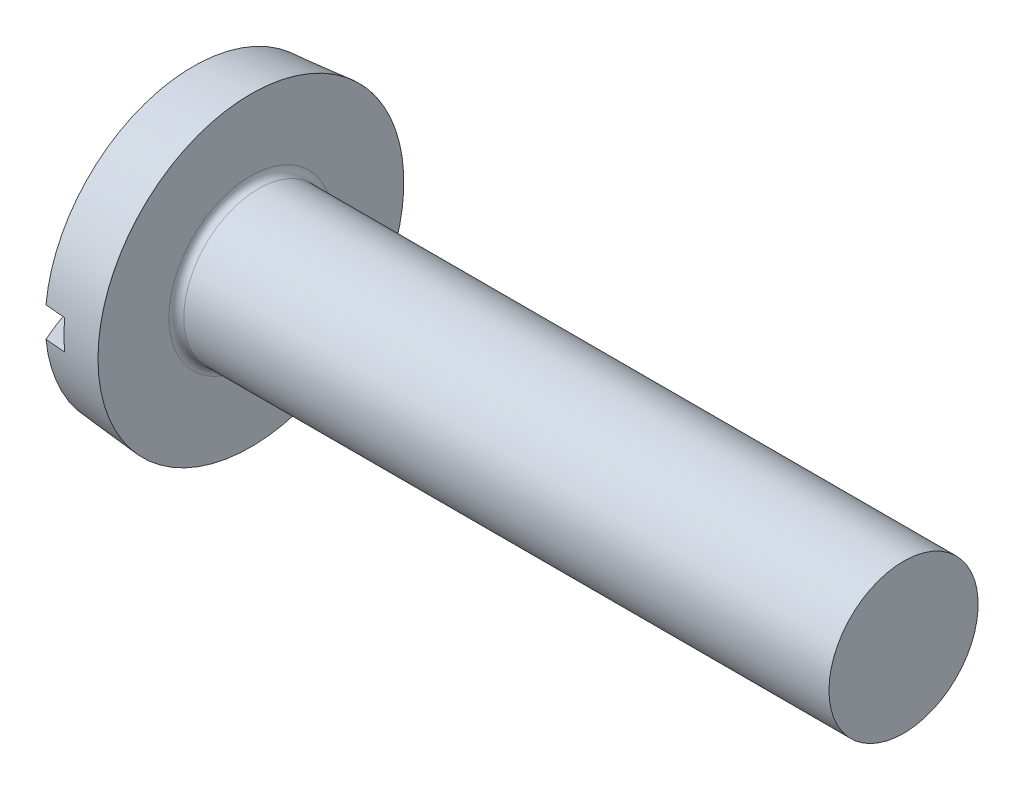
SolidWorks part; units mm, degrees
ref_plane "Plane1" through (0, 0, 0) normal (0, 0, 1) x (1, 0, 0)
ref_plane "Plane2" through (0, 0, 0) normal (0, 1, 0) x (1, 0, 0)
ref_plane "Plane3" through (0, 0, 0) normal (1, 0, 0) x (0, 0, -1)
sketch "BodySke" plane through (0, 0, 0) normal (0, 0, 1) x (1, 0, 0)
  line L0 (4.8, 4) -> (4.8, 8.2)
  line L1 (4.8, 8.2) -> (4.79, 8.2)
  line L2 (-25.4, 0) -> (127, 0) construction
  line L4 (4.8, 4) -> (39.8, 4)
  line L5 (39.8, 4) -> (39.8, 0)
  line L6 (39.8, 0) -> (0, 0)
  line L7 (4.8, -4) -> (39.8, -4) construction
  line L8 (6.05, 6.35) -> (6.05, -3.175) construction
  line L9 (9.8, 6.35) -> (9.8, -3.175) construction
  line L10 (4.79, 8.2) -> (1.7, 7.9297)
  arc A0 (0, 0) -> (1.7, 7.9297) centre (19.344, 0) cw
  dimension "Oval_ht" = 1.7
  dimension "Head_ht" = 4.8
  dimension "Diameter" = 8
  dimension "Length" = 35
  dimension "Advance" = 1.25
  dimension "Thread_nom" = 30
  dimension "Head_ang" = 85
  dimension "D1" = 0.01
  dimension "Head_dia" = 16.4
revolve "Base-Revolve" add sketch "BodySke"
cosmetic thread "ThreadCosmetic" [suppressed]
fillet "Fillet1" radius 0.4 1 edges at (4.8, 0, 4)
sketch "Sketch2" plane through (0, 0, 0) normal (1, 0, 0) x (0, 0, -1)
  line L0 (8.2, -0.8) -> (8.2, 0.8)
  line L1 (8.2, 0.8) -> (-8.2, 0.8)
  line L2 (-8.2, 0.8) -> (-8.2, -0.8)
  line L3 (-8.2, -0.8) -> (8.2, -0.8)
  dimension "D1" = 16.4
  dimension "D2" = 8.2
  dimension "D3" = 0.8
  dimension "Slot_width" = 1.6
extrude "Slot" cut sketch "Sketch2" along normal blind 2.8
sketch "ThdSchSke" plane through (0, 0, 0) normal (0, 0, 1) x (1, 0, 0)
  line L0 (9.8, -3.3095) -> (9.3165, -4)
  line L1 (9.8, -3.3095) -> (10.2835, -4)
  line L2 (10.2835, -4) -> (10.2835, -5)
  line L3 (-3.175, 0) -> (5.1513, 0) construction
  line L5 (10.2835, -5) -> (9.3165, -5)
  line L6 (9.3165, -5) -> (9.3165, -4)
  dimension "Diameter" = 8
  dimension "SideAngle" = 55
  dimension "VeeAngle" = 70
  dimension "Thread_minor" = 6.619
  dimension "Overcut" = 10
  dimension "Start" = 9.8
revolve "ThreadSchematic" [suppressed] cut sketch "ThdSchSke" angle 360 about L3
pattern_linear "ThdSchPat" [suppressed]
equation "' \"Diameter@BodySke\" = 8"
equation "' \"Length@BodySke\" = 35"
equation "' \"Head_dia@BodySke\" = 16.4"
equation "' \"Oval_ht@BodySke\" = 1.7"
equation "' \"Head_ht@BodySke\" = 4.8"
equation "' \"Thread_nom@BodySke\" =  30"
equation "' \"Thread_nom@BodySke\" = 30"
equation "' \"Head_ang@BodySke\" = 85"
equation "' \"Slot_width@Sketch2\" = 1.6"
equation "' \"Slot_depth@Slot\" = 2.8"
equation "' \"Thread_minor@ThreadCosmetic\" = 6.619"
equation "' \"Advance@BodySke\" = 1.25"
equation "\"D1@Sketch2\" = \"Head_dia@BodySke\""
equation "\"D2@Sketch2\" = \"D1@Sketch2\" / 2"
equation "\"D3@Sketch2\" = \"Slot_width@Sketch2\" / 2"
equation "\"Thread_length@ThreadCosmetic\" = ((sgn( (\"Length@BodySke\" - \"Advance@BodySke\" * 2 ) - \"Thread_nom@BodySke\" )-1)*( (\"Length@BodySke\" - \"Advance@BodySke\" * 2 ) - \"Thread_nom@BodySke\" ))/-2+ \"Thread_nom@BodySke\""
equation "\"Thread_minor@ThdSchSke\" = \"Thread_minor@ThreadCosmetic\""
equation "\"Diameter@ThdSchSke\" = \"Diameter@BodySke\""
equation "\"Overcut@ThdSchSke\" = \"Diameter@BodySke\" * 1.25"
equation "\"Start@ThdSchSke\" = \"Head_ht@BodySke\" + \"Length@BodySke\" - \"Thread_length@ThreadCosmetic\"  '---Non-countersunk---"
equation "\"Num_threads@ThdSchPat\" = int( \"Thread_length@ThreadCosmetic\" / \"Advance@BodySke\" + 0.999 )  + 1"
equation "\"Advance@ThdSchPat\" = \"Thread_length@ThreadCosmetic\" /  (\"Num_threads@ThdSchPat\" - 1) 'relax it"
